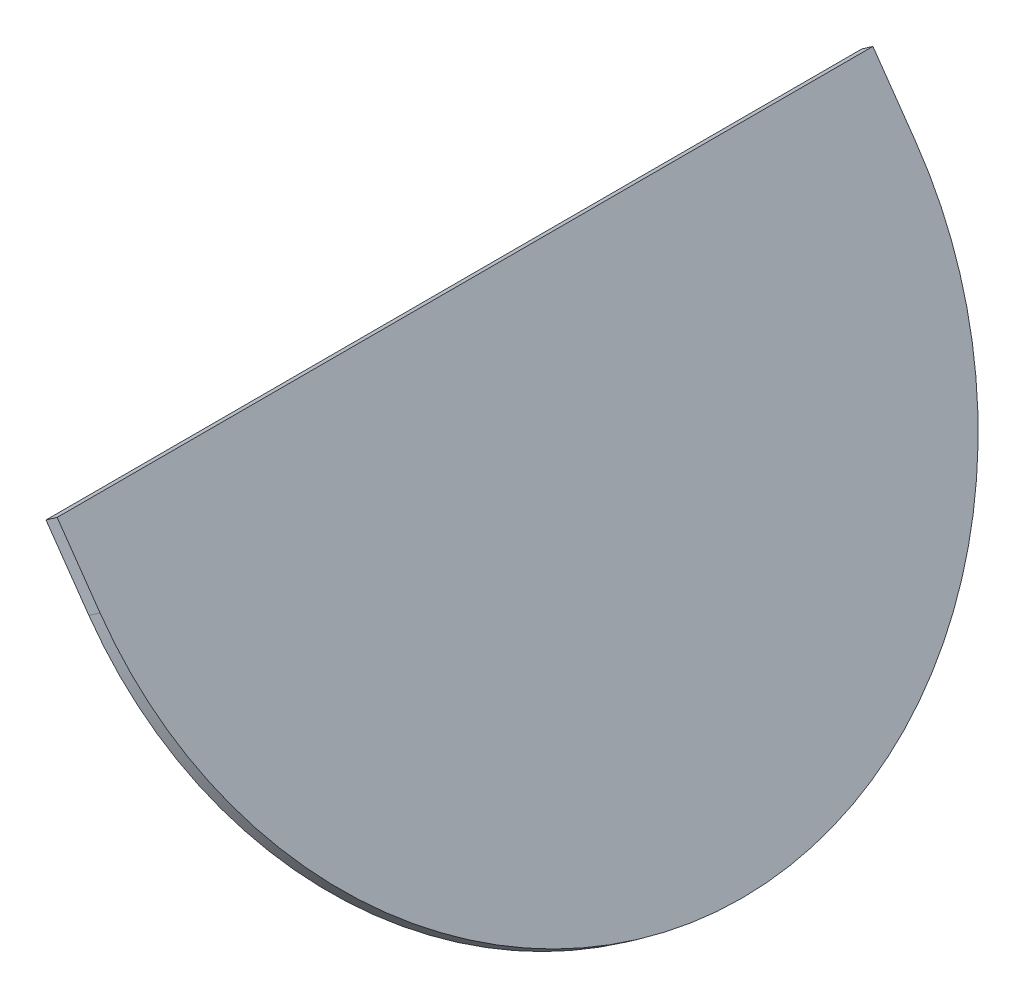
SolidWorks part; units mm, degrees
ref_plane "Front Plane" through (0, 0, 0) normal (0, 0, 1) x (1, 0, 0)
ref_plane "Top Plane" through (0, 0, 0) normal (0, 1, 0) x (1, 0, 0)
ref_plane "Right Plane" through (0, 0, 0) normal (1, 0, 0) x (0, 0, -1)
ref_plane "Plane1" through (921.0037, 644.8938, 0) normal (0.8192, 0.5736, 0) x (0, 0, -1)
sketch "Sketch2" plane through (921.0037, 644.8938, 0) normal (0.8192, 0.5736, 0) x (0, 0, -1)
  line L0 (-1332.1474, 341.1763) -> (-1332.1474, 330.1763)
  line L1 (-1332.1474, 341.1763) -> (-1332.1474, 211.1763) construction
  line L2 (-1212.1474, 341.1763) -> (-1212.1474, 330.1763)
  line L3 (-1212.1474, 341.1763) -> (-1212.1474, 211.1763) construction
  line L4 (-1332.1474, 341.1763) -> (-1212.1474, 341.1763)
  arc A0 (-1332.1474, 330.1763) -> (-1212.1474, 330.1763) centre (-1272.1474, 330.1763) ccw
  dimension "D1" = 11
  dimension "D2" = 11
extrude "Boss-Extrude1" add sketch "Sketch2" against normal blind 2
